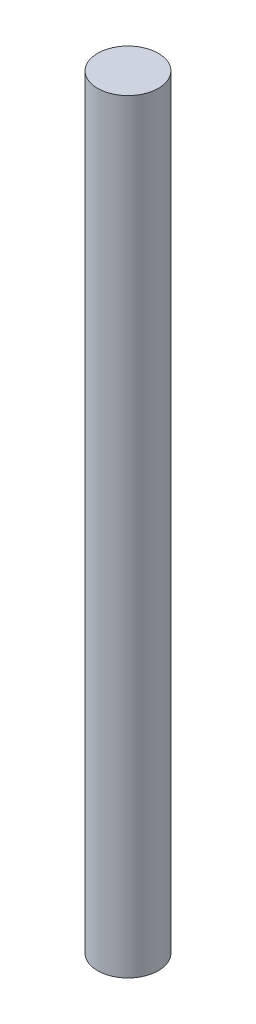
SolidWorks part; units mm, degrees
ref_plane "Front Plane" through (0, 0, 0) normal (0, 0, 1) x (1, 0, 0)
ref_plane "Top Plane" through (0, 0, 0) normal (0, 1, 0) x (1, 0, 0)
ref_plane "Right Plane" through (0, 0, 0) normal (1, 0, 0) x (0, 0, -1)
sketch "Sketch1" plane through (0, 0, 0) normal (0, 1, 0) x (1, 0, 0)
  circle A0 centre (0, 0) radius 3.975
  dimension "D1" = 7.95
extrude "Boss-Extrude1" add sketch "Sketch1" along normal blind 100
